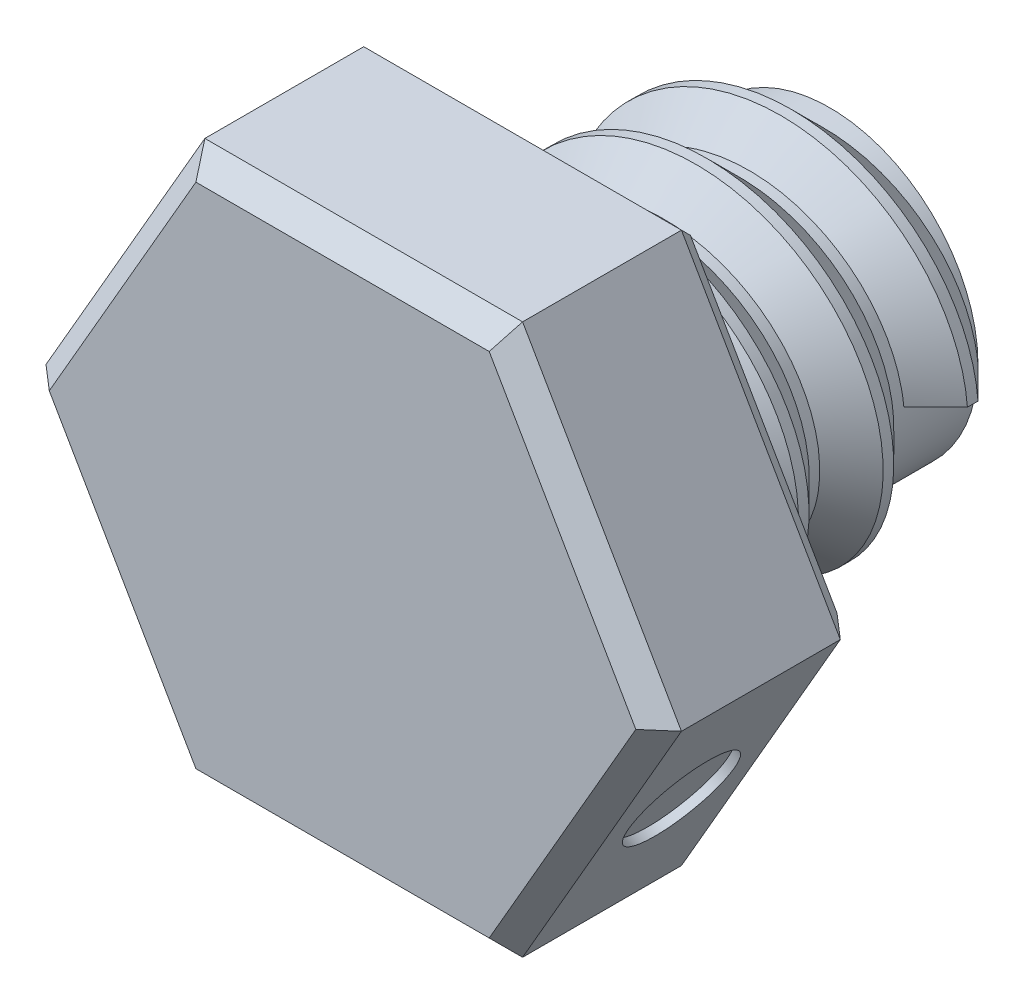
SolidWorks part; units mm, degrees
ref_plane "前视基准面" through (0, 0, 0) normal (0, 0, 1) x (1, 0, 0)
ref_plane "上视基准面" through (0, 0, 0) normal (0, 1, 0) x (1, 0, 0)
ref_plane "右视基准面" through (0, 0, 0) normal (1, 0, 0) x (0, 0, -1)
sketch "草图1" plane through (0, 0, 0) normal (0, 0, 1) x (1, 0, 0)
  line L1 (15, 0) -> (7.5, 12.9904)
  line L2 (7.5, 12.9904) -> (-7.5, 12.9904)
  line L3 (-7.5, 12.9904) -> (-15, 0)
  line L4 (-15, 0) -> (-7.5, -12.9904)
  line L5 (-7.5, -12.9904) -> (7.5, -12.9904)
  line L6 (7.5, -12.9904) -> (15, 0)
  circle A0 centre (0, 0) radius 15
  circle A1 centre (0, 0) radius 12.9904 construction
  dimension "D1" = 30
extrude "凸台-拉伸1" add sketch "草图1" along normal blind 9.5 contours L2 L3 L4 L5 L6 L1
sketch "草图2" plane through (0, 0, 0) normal (0, 0, -1) x (-1, 0, 0)
  circle A0 centre (0, 0) radius 7
  circle A1 centre (0, 0) radius 9
  dimension "D1" = 14
  dimension "D2" = 2
sketch "草图6" plane through (0, 0, 0) normal (0, 0, -1) x (-1, 0, 0)
  circle A0 centre (0, 0) radius 7 construction
  circle A1 centre (0, 0) radius 7
extrude "凸台-拉伸2" add sketch "草图6" along normal blind 13.5
sketch "草图5" plane through (0, 0, 0) normal (0, 0, -1) x (-1, 0, 0)
  circle A0 centre (0, 0) radius 7 construction
  circle A1 centre (0, 0) radius 7
ref_plane "基准面1" through (0, 0, -1.75) normal (0, 0, -1) x (-1, 0, 0)
sketch "草图7" plane through (0, 0, -1.75) normal (0, 0, -1) x (-1, 0, 0)
  circle A0 centre (0, 0) radius 7 construction
  circle A1 centre (0, 0) radius 7
curve "螺旋线/涡状线2" pitch 4 height 10 turns 2.5
sketch "草图8" plane through (0, 0, 0) normal (0, 1, 0) x (1, 0, 0)
  line L0 (-7, 3.5) -> (-7, 0)
  line L1 (-7, 0) -> (-8.5, 1.5)
  line L2 (-8.5, 1.5) -> (-8.5, 2)
  line L3 (-8.5, 2) -> (-7, 3.5)
  point P7 (-7, 1.75)
  dimension "D1" = 1.5
  dimension "D2" = 3.5
  dimension "D3" = 45
  dimension "D4" = 45
sweep "扫描1" add profiles "草图8" path "螺旋线/涡状线2"
sketch "草图9" plane through (0, 0, 0) normal (0, 1, 0) x (1, 0, 0)
  line L0 (9, 0) -> (-9, 0) construction
  line L1 (0, 0) -> (0, 50000) construction
  line L2 (7, 0) -> (7, 2) construction
  line L3 (7, 3.5) -> (7, 0)
  line L4 (7, 3.5) -> (8.5, 2)
  line L5 (8.5, 2) -> (8.5, 1.5)
  line L6 (8.5, 1.5) -> (7, 0)
  point P8 (11.4749, 6.2988)
  dimension "D1" = 3.5
  dimension "D2" = 45
  dimension "D3" = 45
  dimension "D4" = 1.5
revolve "旋转2" add sketch "草图9" angle 45 about L1
chamfer "倒角1" distance 1 angle 45 12 edges at (0, -12.9904, 0) (11.25, -6.4952, 0) (-11.25, -6.4952, 0) (-11.25, 6.4952, 0) (0, 12.9904, 0) (11.25, 6.4952, 0) (-11.25, 6.4952, 9.5) (-11.25, -6.4952, 9.5) (0, -12.9904, 9.5) (11.25, -6.4952, 9.5) (11.25, 6.4952, 9.5) (0, 12.9904, 9.5)
sketch "草图11" plane through (-11.25, -6.4952, 0) normal (-0.866, -0.5, 0) x (0, 0, 1)
  line L0 (1, 0) -> (8.5, 0) construction
  line L8 (1, 7.5) -> (1, -7.5) construction
  line L9 (8.5, -7.5) -> (8.5, 7.5) construction
  line L10 (2.25, 0) -> (7.25, 2.8868)
  line L11 (7.25, 2.8868) -> (7.25, -2.8868)
  line L12 (7.25, -2.8868) -> (2.25, 0)
  line L13 (2.25, 0) -> (7.25, 0) construction
  line L14 (4.75, 0) -> (4.75, -1.2379) construction
  point P12 (4.75, 0)
  dimension "D1" = 5
extrude "切除-拉伸2" cut sketch "草图11" against normal blind 0.4
sketch "草图12" plane through (0, -12.9904, 0) normal (0, -1, 0) x (1, 0, 0)
  line L0 (0, 8.5) -> (0, 1) construction
  line L1 (7.5, 8.5) -> (-7.5, 8.5) construction
  line L2 (-7.5, 1) -> (7.5, 1) construction
  line L3 (-2.5, 7.25) -> (2.5, 2.25) construction
  line L4 (2.5, 2.25) -> (-2.5, 2.25)
  line L5 (2.5, 2.25) -> (2.5, 7.25)
  line L6 (2.5, 7.25) -> (-2.5, 7.25)
  line L7 (-2.5, 2.25) -> (-2.5, 7.25)
  line L8 (0, 7.25) -> (0, 2.25) construction
  line L9 (2.5, 4.75) -> (-2.5, 4.75) construction
  line L10 (2.5, 7.25) -> (-2.5, 2.25) construction
  line L11 (-2.5, 6.8257) -> (2.0757, 2.25)
  line L12 (-2.0757, 7.25) -> (2.5, 2.6743)
  line L13 (2.0757, 7.25) -> (-2.5, 2.6743)
  line L14 (2.5, 6.8257) -> (-2.0757, 2.25)
  line L15 (-2.7121, 7.0379) -> (2.2879, 2.0379) construction
  line L16 (-2.2879, 7.4621) -> (2.7121, 2.4621) construction
  line L17 (2.2879, 7.4621) -> (-2.7121, 2.4621) construction
  line L18 (2.7121, 7.0379) -> (-2.2879, 2.0379) construction
  line L19 (-2.5, 6.8257) -> (-2.0757, 7.25)
  line L20 (2.0757, 7.25) -> (2.5, 6.8257)
  line L21 (-2.5, 2.6743) -> (-2.0757, 2.25)
  line L22 (2.0757, 2.25) -> (2.5, 2.6743)
  point P6 (0, 4.75)
  dimension "D1" = 5
  dimension "D2" = 0.3
  dimension "D3" = 0.3
  dimension "D4" = 0.3
  dimension "D5" = 0.3
sketch "草图13" plane through (11.25, -6.4952, 0) normal (0.866, -0.5, 0) x (0, 0, -1)
  line L0 (-8.5, 0) -> (-1, 0) construction
  line L1 (-8.5, 7.5) -> (-8.5, -7.5) construction
  line L2 (-1, -7.5) -> (-1, 7.5) construction
  circle A0 centre (-4.75, 0) radius 2.5
  dimension "D1" = 5
sketch "草图14" plane through (-11.25, 6.4952, 0) normal (-0.866, 0.5, 0) x (0, 0, 1)
  line L0 (1, 0) -> (8.5, 0) construction
  line L1 (1, 7.5) -> (1, -7.5) construction
  line L2 (8.5, -7.5) -> (8.5, 7.5) construction
  line L4 (7.25, -2.5) -> (2.25, -2.5)
  line L5 (7.25, -2.5) -> (7.25, 2.5)
  line L6 (7.25, 2.5) -> (2.25, 2.5)
  line L7 (2.25, -2.5) -> (2.25, 2.5)
  line L8 (4.75, 2.5) -> (4.75, -2.5) construction
  line L9 (7.25, 0) -> (2.25, 0) construction
  point P6 (4.75, 0)
  dimension "D1" = 5
extrude "切除-拉伸3" cut sketch "草图13" against normal blind 0.4 contours A0
extrude "切除-拉伸4" cut sketch "草图12" against normal blind 0.4 contours L13 L21 L14 L11 | L20 L13 L12 L14
extrude "切除-拉伸5" cut sketch "草图14" against normal blind 0.4 contours L6 L7 L4 L5
